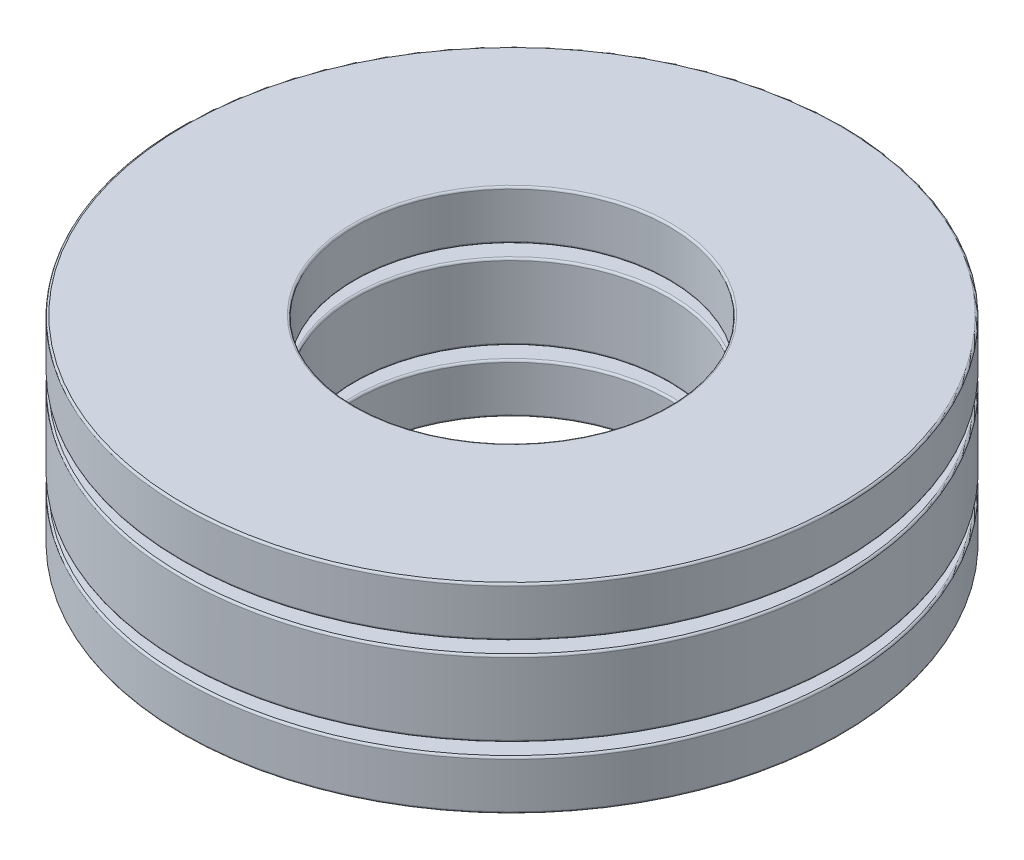
SolidWorks part; units mm, degrees
ref_plane "Front Plane" through (0, 0, 0) normal (0, 0, 1) x (1, 0, 0)
ref_plane "Top Plane" through (0, 0, 0) normal (0, 1, 0) x (1, 0, 0)
ref_plane "Right Plane" through (0, 0, 0) normal (1, 0, 0) x (0, 0, -1)
sketch "Sketch1" plane through (0, 0, 0) normal (0, 1, 0) x (1, 0, 0)
  circle A0 centre (0, 0) radius 10.5 construction
  circle A1 centre (0, 0) radius 5 construction
  circle A2 centre (0, 0) radius 7.55 construction
  dimension "B | OD" = 21
  dimension "A | ID" = 10
  dimension "C | Ball Circle" = 15.1
sketch "Sketch2" plane through (0, 0, 0) normal (0, 0, -1) x (-1, 0, 0)
  line L0 (-10.5, 3.175) -> (-10.5, 1.605) construction
  line L1 (-10.5, 0) -> (0, 0) construction
  line L3 (0, 3.175) -> (0, -3.175) construction
  line L4 (-10.5, 1.605) -> (-10.5, -1.605) construction
  line L6 (-10.5, -1.605) -> (-10.5, -3.175) construction
  point P11 (-10.5, 0)
  dimension "E | Thickness" = 6.35
  dimension "D | Washer Thickness" = 1.57
sketch "Sketch3" plane through (0, 0, 0) normal (0, 0, 1) x (1, 0, 0)
  line L2 (10.5, 1.2038) -> (5, 1.2038)
  line L4 (10.5, 1.2038) -> (10.5, -1.2037)
  line L7 (10.5, -1.2037) -> (5, -1.2037)
  line L8 (5, 1.2038) -> (5, -1.2037)
  line L11 (10.5, 1.605) -> (10.5, -1.605) construction
  point P8 (5, 0)
  dimension "D1" = 2.4075
revolve "Revolve1" add sketch "Sketch3" angle 360 about L3
sketch "Sketch4" plane through (0, 0, 0) normal (0, 0, 1) x (1, 0, 0)
  line L0 (7.55, 1.605) -> (7.55, -1.605)
  arc A0 (7.55, 1.605) -> (7.55, -1.605) centre (7.55, 0) ccw
revolve "Cut-Revolve1" cut sketch "Sketch4" angle 360 about L0
sketch "Sketch5" plane through (0, 0, 0) normal (0, 0, 1) x (1, 0, 0)
  line L0 (7.55, 1.605) -> (7.55, -1.605)
  arc A0 (7.55, 1.605) -> (7.55, -1.605) centre (7.55, 0) ccw
revolve "Revolve2" add sketch "Sketch5" angle 360 about L0
pattern_circular "CirPattern1" count 6 every 60 about axis through (0, 3.175, 0) along (0, -1, 0) of bodies 187
pattern_circular "CirPattern2" count 6 every 60 about axis through (0, 0, 0) along (0, 1, 0) of "Cut-Revolve1"
sketch "Sketch6" plane through (0, 0, 0) normal (0, 0, 1) x (1, 0, 0)
  line L2 (10.5, 3.175) -> (5, 3.175)
  line L3 (10.5, 3.175) -> (10.5, 1.605)
  line L4 (10.5, 1.605) -> (5, 1.605)
  line L5 (5, 3.175) -> (5, 1.605)
  line L6 (10.5, -1.605) -> (5, -1.605)
  line L7 (10.5, -1.605) -> (10.5, -3.175)
  line L8 (10.5, -3.175) -> (5, -3.175)
  line L13 (5, -1.605) -> (5, -3.175)
  point P11 (5, 0)
revolve "Revolve3" add sketch "Sketch6" angle 360 about L3
fillet "Fillet1" radius 0.0635 4 edges at (0, 1.605, 5) (0, 1.605, 10.5) (0, 3.175, 10.5) (0, 3.175, 5)
fillet "Fillet2" radius 0.0635 16 edges at (0, -1.2037, 5) (0, -1.2037, 10.5) (7.55, -1.2037, 1.0616) (2.8556, -1.2037, 7.0693) (-4.6944, -1.2037, 6.0077) (-7.55, -1.2037, -1.0616) (-2.8556, -1.2037, -7.0693) (4.6944, -1.2037, -6.0077) (0, 1.2038, 10.5) (0, 1.2038, 5) (7.55, 1.2038, -1.0616) (4.6944, 1.2038, 6.0077) (-2.8556, 1.2038, 7.0693) (-7.55, 1.2038, 1.0616) (-4.6944, 1.2038, -6.0077) (2.8556, 1.2038, -7.0693)
fillet "Fillet3" radius 0.0635 4 edges at (0, -1.605, 10.5) (0, -1.605, 5) (0, -3.175, 5) (0, -3.175, 10.5)
equation "\"Angle@CirPattern1\" = 360/\"Balls@CirPattern1\""
equation "\"D1@CirPattern2\" = \"Balls@CirPattern1\""
equation "\"D2@CirPattern2\" = \"Angle@CirPattern1\""
equation "\"D1@Sketch3\"=(\"E | Thickness@Sketch2\"-(2*\"D | Washer Thickness@Sketch2\"))*.75"
equation "\"D1@Fillet1\"=\"E | Thickness@Sketch2\" * .01"
equation "\"D1@Fillet2\"=\"D1@Fillet1\""
equation "\"D1@Fillet3\"=\"D1@Fillet1\""
